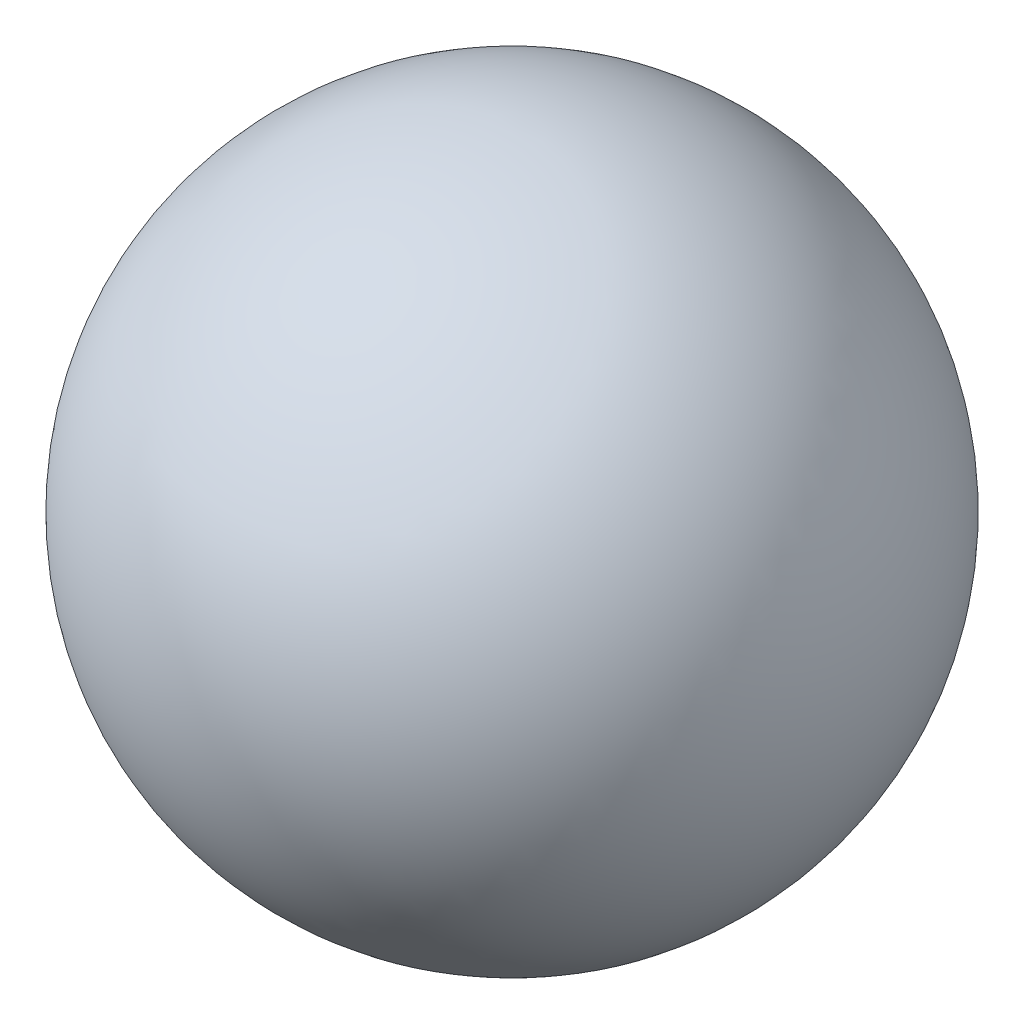
SolidWorks part; units mm, degrees
ref_plane "Front" through (0, 0, 0) normal (0, 0, 1) x (1, 0, 0)
ref_plane "Top" through (0, 0, 0) normal (0, 1, 0) x (1, 0, 0)
ref_plane "Right" through (0, 0, 0) normal (1, 0, 0) x (0, 0, -1)
sketch "Sketch2" plane through (0, 0, 0) normal (1, 0, 0) x (0, 0, -1)
  line L0 (0, -2.25) -> (0, 2.25)
  circle A0 centre (0, 0) radius 2.25 construction
  arc A1 (0, 2.25) -> (0, -2.25) centre (0, 0) cw
  dimension "D1" = 4.5
revolve "Revolve1" add sketch "Sketch2" angle 360 about L0
sketch "Right Plane Cut Guide" plane through (0, 0, 0) normal (1, 0, 0) x (0, 0, -1)
  line L0 (-1.35, 2.25) -> (1.35, 2.25)
  line L1 (1.35, 2.25) -> (1.7642, 1.8358)
  line L2 (2.35, 0.4216) -> (2.35, -0.4216)
  line L3 (-1.35, 2.25) -> (-1.7642, 1.8358)
  line L4 (-2.35, 0.4216) -> (-2.35, -0.4216)
  line L5 (0, 0) -> (0, 2.25) construction
  line L6 (0, 0) -> (-2.35, 0) construction
  line L7 (-1.35, -2.25) -> (-1.7642, -1.8358)
  line L8 (-1.35, -2.25) -> (1.35, -2.25)
  line L9 (1.35, -2.25) -> (1.7642, -1.8358)
  arc A0 (1.7642, -1.8358) -> (2.35, -0.4216) centre (0.35, -0.4216) ccw
  arc A1 (-1.7642, -1.8358) -> (-2.35, -0.4216) centre (-0.35, -0.4216) cw
  arc A2 (1.7642, 1.8358) -> (2.35, 0.4216) centre (0.35, 0.4216) cw
  circle A3 centre (0, 0) radius 2.35 construction
  arc A4 (-1.7642, 1.8358) -> (-2.35, 0.4216) centre (-0.35, 0.4216) ccw
  circle A5 centre (0, 0) radius 2.25 construction
  circle A6 centre (0, 0) radius 2.25 construction
  point P5 (0, 2.35)
  point P14 (2.35, 0)
  point P17 (2.35, -1.25)
  point P20 (-2.35, -1.25)
  point P23 (2.35, 1.25)
  point P26 (-2.35, 1.25)
  dimension "D1" = 4.7
  dimension "D5" = 2
  dimension "D2" = 45
  dimension "D3" = 1
